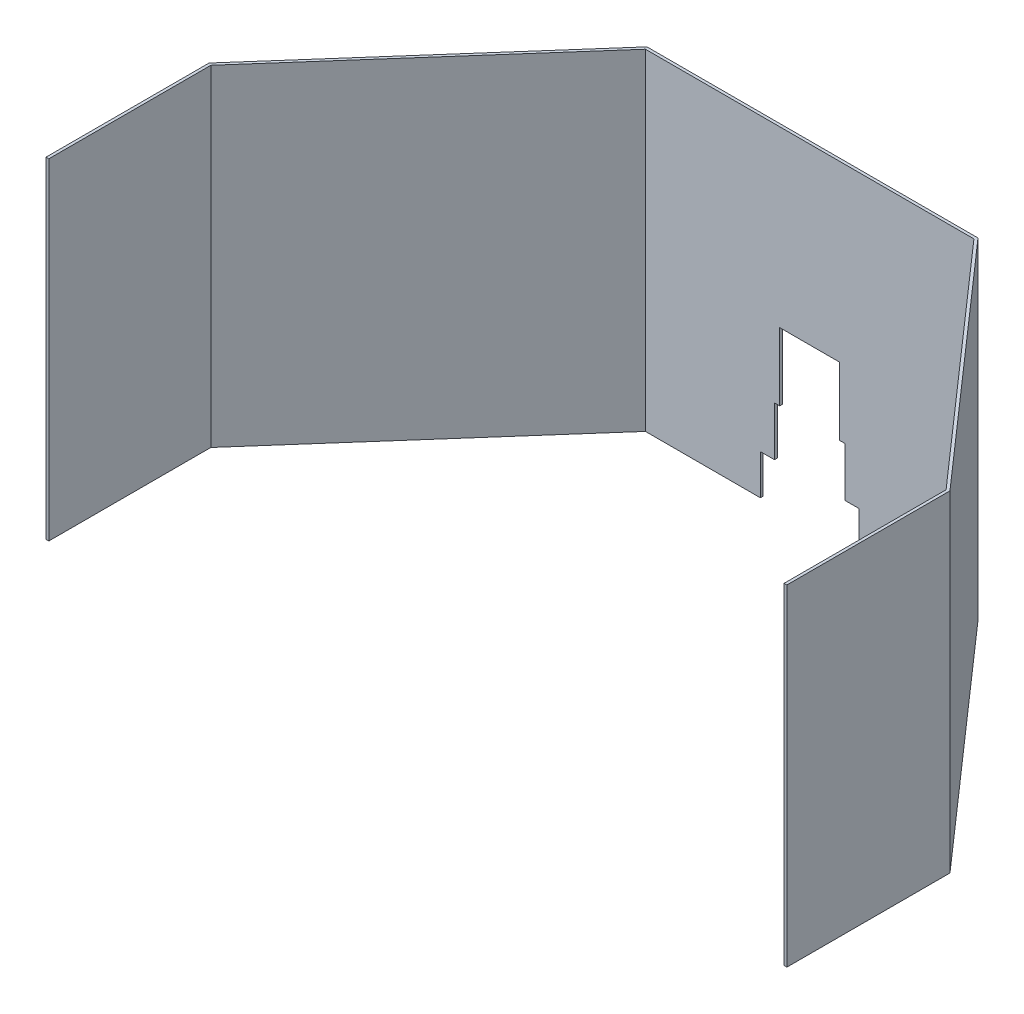
SolidWorks part; units mm, degrees
ref_plane "Front Plane" through (0, 0, 0) normal (0, 0, 1) x (1, 0, 0)
ref_plane "Top Plane" through (0, 0, 0) normal (0, 1, 0) x (1, 0, 0)
ref_plane "Right Plane" through (0, 0, 0) normal (1, 0, 0) x (0, 0, -1)
sketch "Sketch1" plane through (0, 0, 0) normal (0, 1, 0) x (1, 0, 0)
  line L0 (-117.5045, 326.1556) -> (117.5045, 326.1556)
  line L3 (-81.7739, 326.1556) -> (86.8843, 326.1556)
  line L4 (-81.7739, 326.1556) -> (-81.7739, 382.1556) construction
  line L5 (-81.7739, 382.1556) -> (86.8843, 382.1556) construction
  line L6 (86.8843, 326.1556) -> (86.8843, 382.1556) construction
  line L9 (-117.5045, 326.1556) -> (-263, 160.7545)
  line L10 (-263, 160.7545) -> (-263, 45.0012)
  line L11 (-263, 45.0012) -> (-261, 45.0012)
  line L12 (-116.6001, 324.1556) -> (116.6001, 324.1556)
  line L15 (-116.6001, 324.1556) -> (-261, 160)
  line L16 (-261, 160) -> (-261, 45.0012)
  line L17 (116.6001, 324.1556) -> (261, 160)
  line L18 (261, 160) -> (261, 45.0035)
  line L19 (261, 45.0035) -> (263, 45.0035)
  line L20 (263, 45.0035) -> (263, 160.7545)
  line L21 (263, 160.7545) -> (117.5045, 326.1556)
  dimension "D1" = 56
  dimension "D2" = 2
extrude "Boss-Extrude5" add sketch "Sketch1" along normal blind 235 contours L18 L19 L20 L21 L0 L9 L10 L11 L16 L15 L12 L17
sketch "Sketch4" plane through (0, 0, -326.1556) normal (0, 0, -1) x (-1, 0, 0)
  line L0 (0, 0) -> (0, 111.5) construction
  line L1 (-117.5045, 235) -> (-117.5045, 0) construction
  line L2 (117.5045, 235) -> (117.5045, 0) construction
  line L3 (-117.5045, 28.4) -> (117.5045, 28.4) construction
  line L4 (154.6349, 0) -> (-154.6349, 0) construction
  line L5 (-117.5045, 63.4) -> (117.5045, 63.4) construction
  line L6 (-117.5045, 111.5) -> (117.5045, 111.5) construction
  line L7 (-35, 28.4) -> (35, 28.4)
  line L8 (-35, 28.4) -> (-35, 0)
  line L9 (-35, 0) -> (35, 0)
  line L10 (35, 28.4) -> (35, 0)
  line L11 (-35, 28.4) -> (35, 0) construction
  line L12 (-35, 0) -> (35, 28.4) construction
  line L14 (-25, 63.4) -> (25, 63.4)
  line L15 (-25, 63.4) -> (-25, 28.4)
  line L16 (-25, 28.4) -> (25, 28.4)
  line L17 (25, 63.4) -> (25, 28.4)
  line L18 (-25, 63.4) -> (25, 28.4) construction
  line L19 (-25, 28.4) -> (25, 63.4) construction
  line L20 (-21.25, 111.5) -> (21.25, 111.5)
  line L21 (-21.25, 111.5) -> (-21.25, 63.4)
  line L22 (-21.25, 63.4) -> (21.25, 63.4)
  line L23 (21.25, 111.5) -> (21.25, 63.4)
  line L24 (-21.25, 111.5) -> (21.25, 63.4) construction
  line L25 (-21.25, 63.4) -> (21.25, 111.5) construction
  point P0 (0, 14.2)
  point P20 (0, 45.9)
  point P25 (0, 87.45)
  line M2 (-117.5045, 0) -> (117.5045, 0)
  dimension "D1" = 28.4
  dimension "D2" = 63.4
  dimension "D3" = 83.1
  dimension "D4" = 70
  dimension "D5" = 50
  dimension "D6" = 42.5
extrude "Cut-Extrude1" cut sketch "Sketch4" against normal up to surface (2 mm away) contours L23 L20 L21 L14 | L17 L14 L15 L7 | L10 L7 L8 M2 up to face at (0, 117.5, -324.1556)
equation "\"gap\"= 1mm"
equation "\"casewidth\"= 2mm"
equation "\"D2@Sketch1\"=\"casewidth\""
equation "\"flatheight\"= 235mm"
equation "\"D1@Boss-Extrude5\"=\"flatheight\""
